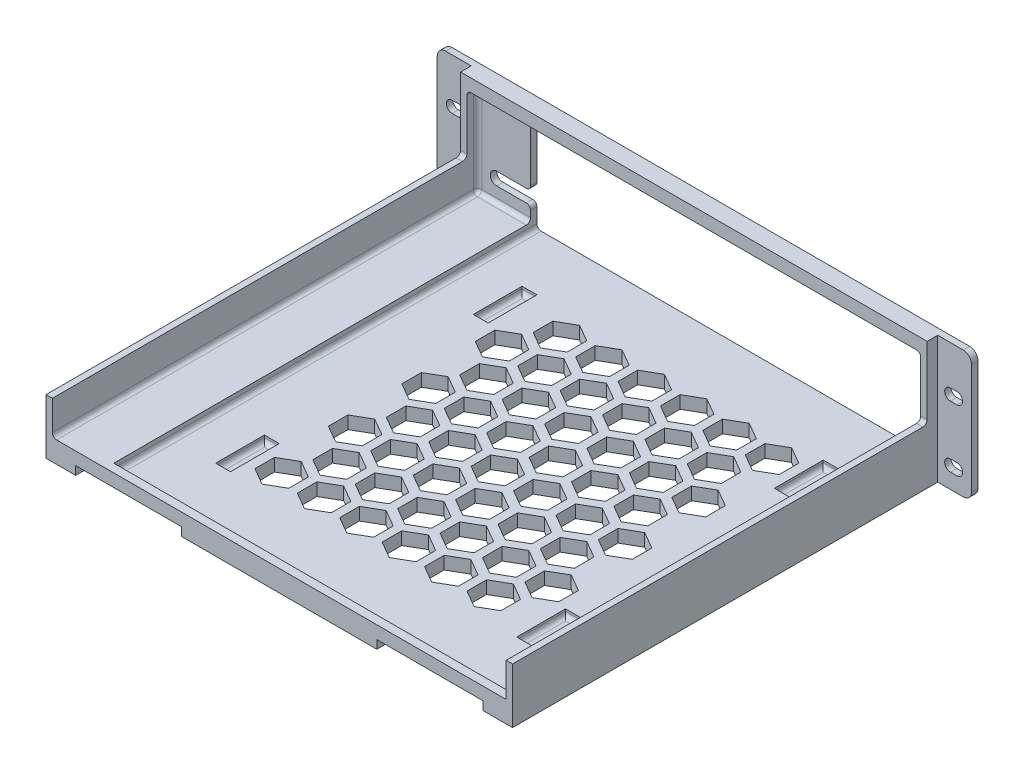
SolidWorks part; units mm, degrees
ref_plane "Front Plane" through (0, 0, 0) normal (0, 0, 1) x (1, 0, 0)
ref_plane "Top Plane" through (0, 0, 0) normal (0, 1, 0) x (1, 0, 0)
ref_plane "Right Plane" through (0, 0, 0) normal (1, 0, 0) x (0, 0, -1)
sketch "Sketch2" plane through (0, 0, 0) normal (0, 0, 1) x (1, 0, 0)
  line L0 (16, 106.2116) -> (16, -100.2906) construction
  line L1 (0, 0) -> (252, 0)
  line L2 (0, 0) -> (0, 60)
  line L3 (0, 60) -> (252, 60)
  line L4 (252, 0) -> (252, 60)
  line L5 (236, 110.5998) -> (236, -45.5674) construction
  line L6 (245, 38.8) -> (242, 38.8) construction
  line L7 (245, 36.1) -> (242, 36.1)
  line L8 (245, 41.5) -> (242, 41.5)
  line L9 (242, 9.8) -> (245, 9.8) construction
  line L10 (242, 12.5) -> (245, 12.5)
  line L11 (242, 7.1) -> (245, 7.1)
  line L12 (7, 38.8) -> (10, 38.8) construction
  line L13 (7, 41.5) -> (10, 41.5)
  line L14 (7, 36.1) -> (10, 36.1)
  line L15 (7, 9.8) -> (10, 9.8) construction
  line L16 (7, 12.5) -> (10, 12.5)
  line L17 (7, 7.1) -> (10, 7.1)
  arc A4 (245, 36.1) -> (245, 41.5) centre (245, 38.8) ccw
  arc A5 (242, 41.5) -> (242, 36.1) centre (242, 38.8) ccw
  arc A6 (242, 12.5) -> (242, 7.1) centre (242, 9.8) ccw
  arc A7 (245, 7.1) -> (245, 12.5) centre (245, 9.8) ccw
  arc A8 (7, 41.5) -> (7, 36.1) centre (7, 38.8) ccw
  arc A9 (10, 36.1) -> (10, 41.5) centre (10, 38.8) ccw
  arc A10 (7, 12.5) -> (7, 7.1) centre (7, 9.8) ccw
  arc A11 (10, 7.1) -> (10, 12.5) centre (10, 9.8) ccw
  point P8 (8.5, 38.8)
  point P17 (243.5, 38.8)
  point P22 (243.5, 9.8)
  point P30 (8.5, 9.8)
  point P37 (0, 0)
  point P38 (0, 0)
  dimension "D5" = 7
  dimension "D10" = 29
  dimension "D6" = 2.7
  dimension "D1" = 16
  dimension "D2" = 16
  dimension "D3" = 220
  dimension "D4" = 60
  dimension "D7" = 6
  dimension "D8" = 7
  dimension "D9" = 21.2
  dimension "D11" = 6
extrude "Boss-Extrude1" add sketch "Sketch2" along normal blind 3
sketch "Sketch3" plane through (0, 0, 3) normal (0, 0, 1) x (1, 0, 0)
  line L0 (0, 0) -> (252, 0) construction
  line L1 (16, 0) -> (236, 0)
  line L2 (16, 0) -> (16, 6)
  line L3 (16, 6) -> (236, 6)
  line L4 (236, 0) -> (236, 6)
  line L7 (16, 0) -> (0, 0) construction
  line L8 (236, 0) -> (252, 0) construction
  dimension "D1" = 220
  dimension "D3" = 6
extrude "Boss-Extrude2" add sketch "Sketch3" along normal blind 200.5
sketch "Sketch6" plane through (0, 0, 0) normal (0, 0, -1) x (-1, 0, 0)
  line L0 (0, 0) -> (-252, 0) construction
  line L1 (-233, 6) -> (-44, 6)
  line L2 (-233, 6) -> (-233, 54)
  line L3 (-233, 54) -> (-44, 54)
  line L4 (-44, 6) -> (-44, 54)
  line L5 (-252, 0) -> (-252, 60) construction
  dimension "D1" = 6
  dimension "D2" = 48
  dimension "D3" = 189
  dimension "D4" = 19
extrude "Cut-Extrude1" cut sketch "Sketch6" against normal blind 4
sketch "Sketch9" plane through (0, 0, 0) normal (0, 0, -1) x (-1, 0, 0)
  line L0 (0, 60) -> (0, 0) construction
  line L2 (-20, 4.4578) -> (-20, 43.1358) construction
  line L5 (-233, 6) -> (-44, 6) construction
  line L6 (-28, 23) -> (-44, 23)
  line L7 (-44, 6) -> (-44, 54) construction
  line L8 (-44, 17) -> (-28, 17)
  line L9 (-44, 23) -> (-44, 17)
  arc A1 (-28, 17) -> (-28, 23) centre (-28, 20) ccw
  dimension "D2" = 6
  dimension "D1" = 20
  dimension "D3" = 14
  dimension "D4" = 16
extrude "Cut-Extrude11" cut sketch "Sketch9" against normal blind 3
sketch "Sketch10" plane through (0, 0, 3) normal (0, 0, 1) x (1, 0, 0)
  line L1 (16, 6) -> (19, 6)
  line L2 (16, 6) -> (16, 26)
  line L3 (16, 26) -> (19, 26)
  line L4 (19, 6) -> (19, 26)
  line L5 (236, 6) -> (233, 6)
  line L6 (236, 6) -> (236, 26)
  line L7 (236, 26) -> (233, 26)
  line L8 (233, 6) -> (233, 26)
  line L9 (233, 54) -> (233, 6) construction
  dimension "D1" = 3
  dimension "D2" = 20
  dimension "D3" = 20
extrude "Boss-Extrude7" add sketch "Sketch10" along normal blind 200.5
sketch "Sketch15" plane through (0, 0, 3) normal (0, 0, 1) x (1, 0, 0)
  line L0 (236, 26) -> (236, 60)
  line L1 (252, 60) -> (0, 60) construction
  line L2 (236, 60) -> (16, 60)
  line L3 (16, 60) -> (16, 26)
  line L4 (16, 26) -> (19, 26)
  line L5 (19, 26) -> (19, 54)
  line L6 (19, 54) -> (233, 54)
  line L7 (233, 54) -> (233, 26)
  line L8 (233, 54) -> (233, 26) construction
  line L9 (233, 26) -> (236, 26)
extrude "Boss-Extrude8" add sketch "Sketch15" along normal blind 5
sketch "Sketch11" plane through (0, 6, 0) normal (0, 1, 0) x (1, 0, 0)
  line L1 (213, -27) -> (206, -27)
  line L2 (213, -27) -> (213, -50)
  line L3 (213, -50) -> (206, -50)
  line L4 (206, -27) -> (206, -50)
  line L5 (233, -203.5) -> (233, 0) construction
  line L6 (44, -3) -> (44, 0) construction
  line L7 (64, -27) -> (71, -27)
  line L8 (64, -27) -> (64, -50)
  line L9 (64, -50) -> (71, -50)
  line L10 (71, -27) -> (71, -50)
  line L11 (213, -171.5) -> (206, -171.5)
  line L12 (213, -171.5) -> (213, -148.5)
  line L13 (213, -148.5) -> (206, -148.5)
  line L14 (206, -171.5) -> (206, -148.5)
  line L15 (64, -148.5) -> (71, -148.5)
  line L16 (64, -148.5) -> (64, -171.5)
  line L17 (64, -171.5) -> (71, -171.5)
  line L18 (71, -148.5) -> (71, -171.5)
  line L19 (233, 0) -> (44, 0) construction
  dimension "D1" = 20
  dimension "D2" = 20
  dimension "D3" = 7
  dimension "D4" = 27
  dimension "D5" = 50
  dimension "D6" = 148.5
  dimension "D7" = 171.5
extrude "Cut-Extrude12" cut sketch "Sketch11" against normal blind 3
sketch "Sketch13" plane through (0, 6, 0) normal (0, 1, 0) x (1, 0, 0)
  line L72 (93.5, -82.5068) -> (91.5, -85.9709) construction
  line L73 (93.5, -47.8658) -> (91.5, -51.3299) construction
  line L74 (95.5, -51.3299) -> (91.5, -51.3299) construction
  line L75 (95.5, -51.3299) -> (93.5, -47.8658) construction
  line L76 (181.5, -43.247) -> (183.5, -46.7111) construction
  line L77 (185.5, -43.247) -> (183.5, -46.7111) construction
  line L78 (185.5, -43.247) -> (181.5, -43.247) construction
  line L79 (95.5, -85.9709) -> (91.5, -85.9709) construction
  line L80 (95.5, -85.9709) -> (93.5, -82.5068) construction
  line L81 (181.5, -77.888) -> (183.5, -81.3521) construction
  line L82 (185.5, -77.888) -> (183.5, -81.3521) construction
  line L83 (185.5, -77.888) -> (181.5, -77.888) construction
  line L84 (91.5, -60.5675) -> (95.5, -60.5675) construction
  line L85 (93.5, -64.0316) -> (91.5, -60.5675) construction
  line L86 (93.5, -64.0316) -> (95.5, -60.5675) construction
  line L87 (93.5, -151.7889) -> (91.5, -155.253) construction
  line L88 (93.5, -117.1479) -> (91.5, -120.612) construction
  line L89 (95.5, -120.612) -> (91.5, -120.612) construction
  line L90 (95.5, -120.612) -> (93.5, -117.1479) construction
  line L91 (181.5, -112.5291) -> (183.5, -115.9932) construction
  line L92 (185.5, -112.5291) -> (183.5, -115.9932) construction
  line L93 (185.5, -112.5291) -> (181.5, -112.5291) construction
  line L94 (95.5, -155.253) -> (91.5, -155.253) construction
  line L95 (95.5, -155.253) -> (93.5, -151.7889) construction
  line L96 (181.5, -147.1701) -> (183.5, -150.6342) construction
  line L97 (185.5, -147.1701) -> (183.5, -150.6342) construction
  line L98 (185.5, -147.1701) -> (181.5, -147.1701) construction
  line L99 (91.5, -129.8496) -> (95.5, -129.8496) construction
  line L100 (93.5, -133.3137) -> (91.5, -129.8496) construction
  line L101 (93.5, -133.3137) -> (95.5, -129.8496) construction
  line L102 (91.5, -95.2085) -> (95.5, -95.2085) construction
  line L103 (93.5, -98.6726) -> (91.5, -95.2085) construction
  line L104 (93.5, -98.6726) -> (95.5, -95.2085) construction
  line L105 (75.5, -168.2118) -> (75.5, -145.0225) construction
  line L106 (201.5, -150.8913) -> (201.5, -127.7019) construction
  line L107 (206, -27) -> (201.5, -27) construction
  line L108 (71, -27) -> (75.5, -27) construction
  line L109 (83.5, -29.3906) -> (183.5, -29.3906) construction
  line L110 (64, -29.3906) -> (64, -27) construction
  line L111 (173.5, -169.1094) -> (73.5, -169.1094) construction
  line L112 (64, -27) -> (64, -50) construction
  line L113 (64, -171.5) -> (64, -169.1094) construction
  line B0 (113.5, -47.8658) -> (121.5, -43.247)
  line B1 (93.5, -47.8658) -> (101.5, -43.247)
  line B2 (101.5, -43.247) -> (101.5, -34.0094)
  line B3 (101.5, -34.0094) -> (93.5, -29.3906)
  line B4 (93.5, -29.3906) -> (85.5, -34.0094)
  line B5 (85.5, -34.0094) -> (85.5, -43.247)
  line B6 (85.5, -43.247) -> (93.5, -47.8658)
  line B7 (121.5, -43.247) -> (121.5, -34.0094)
  line B8 (121.5, -34.0094) -> (113.5, -29.3906)
  line B9 (113.5, -29.3906) -> (105.5, -34.0094)
  line B10 (105.5, -34.0094) -> (105.5, -43.247)
  line B11 (105.5, -43.247) -> (113.5, -47.8658)
  line B12 (133.5, -47.8658) -> (141.5, -43.247)
  line B13 (141.5, -43.247) -> (141.5, -34.0094)
  line B14 (141.5, -34.0094) -> (133.5, -29.3906)
  line B15 (133.5, -29.3906) -> (125.5, -34.0094)
  line B16 (125.5, -34.0094) -> (125.5, -43.247)
  line B17 (125.5, -43.247) -> (133.5, -47.8658)
  line B18 (153.5, -47.8658) -> (161.5, -43.247)
  line B19 (161.5, -43.247) -> (161.5, -34.0094)
  line B20 (161.5, -34.0094) -> (153.5, -29.3906)
  line B21 (153.5, -29.3906) -> (145.5, -34.0094)
  line B22 (145.5, -34.0094) -> (145.5, -43.247)
  line B23 (145.5, -43.247) -> (153.5, -47.8658)
  line B24 (173.5, -47.8658) -> (181.5, -43.247)
  line B25 (181.5, -43.247) -> (181.5, -34.0094)
  line B26 (181.5, -34.0094) -> (173.5, -29.3906)
  line B27 (173.5, -29.3906) -> (165.5, -34.0094)
  line B28 (165.5, -34.0094) -> (165.5, -43.247)
  line B29 (165.5, -43.247) -> (173.5, -47.8658)
  line B30 (193.5, -47.8658) -> (201.5, -43.247)
  line B31 (201.5, -43.247) -> (201.5, -34.0094)
  line B32 (201.5, -34.0094) -> (193.5, -29.3906)
  line B33 (193.5, -29.3906) -> (185.5, -34.0094)
  line B34 (185.5, -34.0094) -> (185.5, -43.247)
  line B35 (185.5, -43.247) -> (193.5, -47.8658)
  circle B36 centre (93.5, -38.6282) radius 8 construction
  circle B37 centre (113.5, -38.6282) radius 8 construction
  circle B38 centre (133.5, -38.6282) radius 8 construction
  circle B39 centre (153.5, -38.6282) radius 8 construction
  circle B40 centre (173.5, -38.6282) radius 8 construction
  circle B41 centre (193.5, -38.6282) radius 8 construction
  line B42 (103.5, -65.1863) -> (111.5, -60.5675)
  line B43 (83.5, -65.1863) -> (91.5, -60.5675)
  line B44 (91.5, -60.5675) -> (91.5, -51.3299)
  line B45 (91.5, -51.3299) -> (83.5, -46.7111)
  line B46 (83.5, -46.7111) -> (75.5, -51.3299)
  line B47 (75.5, -51.3299) -> (75.5, -60.5675)
  line B48 (75.5, -60.5675) -> (83.5, -65.1863)
  line B49 (111.5, -60.5675) -> (111.5, -51.3299)
  line B50 (111.5, -51.3299) -> (103.5, -46.7111)
  line B51 (103.5, -46.7111) -> (95.5, -51.3299)
  line B52 (95.5, -51.3299) -> (95.5, -60.5675)
  line B53 (95.5, -60.5675) -> (103.5, -65.1863)
  line B54 (123.5, -65.1863) -> (131.5, -60.5675)
  line B55 (131.5, -60.5675) -> (131.5, -51.3299)
  line B56 (131.5, -51.3299) -> (123.5, -46.7111)
  line B57 (123.5, -46.7111) -> (115.5, -51.3299)
  line B58 (115.5, -51.3299) -> (115.5, -60.5675)
  line B59 (115.5, -60.5675) -> (123.5, -65.1863)
  line B60 (143.5, -65.1863) -> (151.5, -60.5675)
  line B61 (151.5, -60.5675) -> (151.5, -51.3299)
  line B62 (151.5, -51.3299) -> (143.5, -46.7111)
  line B63 (143.5, -46.7111) -> (135.5, -51.3299)
  line B64 (135.5, -51.3299) -> (135.5, -60.5675)
  line B65 (135.5, -60.5675) -> (143.5, -65.1863)
  line B66 (163.5, -65.1863) -> (171.5, -60.5675)
  line B67 (171.5, -60.5675) -> (171.5, -51.3299)
  line B68 (171.5, -51.3299) -> (163.5, -46.7111)
  line B69 (163.5, -46.7111) -> (155.5, -51.3299)
  line B70 (155.5, -51.3299) -> (155.5, -60.5675)
  line B71 (155.5, -60.5675) -> (163.5, -65.1863)
  line B72 (183.5, -65.1863) -> (191.5, -60.5675)
  line B73 (191.5, -60.5675) -> (191.5, -51.3299)
  line B74 (191.5, -51.3299) -> (183.5, -46.7111)
  line B75 (183.5, -46.7111) -> (175.5, -51.3299)
  line B76 (175.5, -51.3299) -> (175.5, -60.5675)
  line B77 (175.5, -60.5675) -> (183.5, -65.1863)
  line B78 (113.5, -82.5068) -> (121.5, -77.888)
  line B79 (93.5, -82.5068) -> (101.5, -77.888)
  line B80 (101.5, -77.888) -> (101.5, -68.6504)
  line B81 (101.5, -68.6504) -> (93.5, -64.0316)
  line B82 (93.5, -64.0316) -> (85.5, -68.6504)
  line B83 (85.5, -68.6504) -> (85.5, -77.888)
  line B84 (85.5, -77.888) -> (93.5, -82.5068)
  line B85 (121.5, -77.888) -> (121.5, -68.6504)
  line B86 (121.5, -68.6504) -> (113.5, -64.0316)
  line B87 (113.5, -64.0316) -> (105.5, -68.6504)
  line B88 (105.5, -68.6504) -> (105.5, -77.888)
  line B89 (105.5, -77.888) -> (113.5, -82.5068)
  line B90 (133.5, -82.5068) -> (141.5, -77.888)
  line B91 (141.5, -77.888) -> (141.5, -68.6504)
  line B92 (141.5, -68.6504) -> (133.5, -64.0316)
  line B93 (133.5, -64.0316) -> (125.5, -68.6504)
  line B94 (125.5, -68.6504) -> (125.5, -77.888)
  line B95 (125.5, -77.888) -> (133.5, -82.5068)
  line B96 (153.5, -82.5068) -> (161.5, -77.888)
  line B97 (161.5, -77.888) -> (161.5, -68.6504)
  line B98 (161.5, -68.6504) -> (153.5, -64.0316)
  line B99 (153.5, -64.0316) -> (145.5, -68.6504)
  line B100 (145.5, -68.6504) -> (145.5, -77.888)
  line B101 (145.5, -77.888) -> (153.5, -82.5068)
  line B102 (173.5, -82.5068) -> (181.5, -77.888)
  line B103 (181.5, -77.888) -> (181.5, -68.6504)
  line B104 (181.5, -68.6504) -> (173.5, -64.0316)
  line B105 (173.5, -64.0316) -> (165.5, -68.6504)
  line B106 (165.5, -68.6504) -> (165.5, -77.888)
  line B107 (165.5, -77.888) -> (173.5, -82.5068)
  line B108 (193.5, -82.5068) -> (201.5, -77.888)
  line B109 (201.5, -77.888) -> (201.5, -68.6504)
  line B110 (201.5, -68.6504) -> (193.5, -64.0316)
  line B111 (193.5, -64.0316) -> (185.5, -68.6504)
  line B112 (185.5, -68.6504) -> (185.5, -77.888)
  line B113 (185.5, -77.888) -> (193.5, -82.5068)
  line B114 (103.5, -99.8274) -> (111.5, -95.2085)
  line B115 (83.5, -99.8274) -> (91.5, -95.2085)
  line B116 (91.5, -95.2085) -> (91.5, -85.9709)
  line B117 (91.5, -85.9709) -> (83.5, -81.3521)
  line B118 (83.5, -81.3521) -> (75.5, -85.9709)
  line B119 (75.5, -85.9709) -> (75.5, -95.2085)
  line B120 (75.5, -95.2085) -> (83.5, -99.8274)
  line B121 (111.5, -95.2085) -> (111.5, -85.9709)
  line B122 (111.5, -85.9709) -> (103.5, -81.3521)
  line B123 (103.5, -81.3521) -> (95.5, -85.9709)
  line B124 (95.5, -85.9709) -> (95.5, -95.2085)
  line B125 (95.5, -95.2085) -> (103.5, -99.8274)
  line B126 (123.5, -99.8274) -> (131.5, -95.2085)
  line B127 (131.5, -95.2085) -> (131.5, -85.9709)
  line B128 (131.5, -85.9709) -> (123.5, -81.3521)
  line B129 (123.5, -81.3521) -> (115.5, -85.9709)
  line B130 (115.5, -85.9709) -> (115.5, -95.2085)
  line B131 (115.5, -95.2085) -> (123.5, -99.8274)
  line B132 (143.5, -99.8274) -> (151.5, -95.2085)
  line B133 (151.5, -95.2085) -> (151.5, -85.9709)
  line B134 (151.5, -85.9709) -> (143.5, -81.3521)
  line B135 (143.5, -81.3521) -> (135.5, -85.9709)
  line B136 (135.5, -85.9709) -> (135.5, -95.2085)
  line B137 (135.5, -95.2085) -> (143.5, -99.8274)
  line B138 (163.5, -99.8274) -> (171.5, -95.2085)
  line B139 (171.5, -95.2085) -> (171.5, -85.9709)
  line B140 (171.5, -85.9709) -> (163.5, -81.3521)
  line B141 (163.5, -81.3521) -> (155.5, -85.9709)
  line B142 (155.5, -85.9709) -> (155.5, -95.2085)
  line B143 (155.5, -95.2085) -> (163.5, -99.8274)
  line B144 (183.5, -99.8274) -> (191.5, -95.2085)
  line B145 (191.5, -95.2085) -> (191.5, -85.9709)
  line B146 (191.5, -85.9709) -> (183.5, -81.3521)
  line B147 (183.5, -81.3521) -> (175.5, -85.9709)
  line B148 (175.5, -85.9709) -> (175.5, -95.2085)
  line B149 (175.5, -95.2085) -> (183.5, -99.8274)
  line B150 (113.5, -117.1479) -> (121.5, -112.5291)
  line B151 (93.5, -117.1479) -> (101.5, -112.5291)
  line B152 (101.5, -112.5291) -> (101.5, -103.2915)
  line B153 (101.5, -103.2915) -> (93.5, -98.6726)
  line B154 (93.5, -98.6726) -> (85.5, -103.2915)
  line B155 (85.5, -103.2915) -> (85.5, -112.5291)
  line B156 (85.5, -112.5291) -> (93.5, -117.1479)
  line B157 (121.5, -112.5291) -> (121.5, -103.2915)
  line B158 (121.5, -103.2915) -> (113.5, -98.6726)
  line B159 (113.5, -98.6726) -> (105.5, -103.2915)
  line B160 (105.5, -103.2915) -> (105.5, -112.5291)
  line B161 (105.5, -112.5291) -> (113.5, -117.1479)
  line B162 (133.5, -117.1479) -> (141.5, -112.5291)
  line B163 (141.5, -112.5291) -> (141.5, -103.2915)
  line B164 (141.5, -103.2915) -> (133.5, -98.6726)
  line B165 (133.5, -98.6726) -> (125.5, -103.2915)
  line B166 (125.5, -103.2915) -> (125.5, -112.5291)
  line B167 (125.5, -112.5291) -> (133.5, -117.1479)
  line B168 (153.5, -117.1479) -> (161.5, -112.5291)
  line B169 (161.5, -112.5291) -> (161.5, -103.2915)
  line B170 (161.5, -103.2915) -> (153.5, -98.6726)
  line B171 (153.5, -98.6726) -> (145.5, -103.2915)
  line B172 (145.5, -103.2915) -> (145.5, -112.5291)
  line B173 (145.5, -112.5291) -> (153.5, -117.1479)
  line B174 (173.5, -117.1479) -> (181.5, -112.5291)
  line B175 (181.5, -112.5291) -> (181.5, -103.2915)
  line B176 (181.5, -103.2915) -> (173.5, -98.6726)
  line B177 (173.5, -98.6726) -> (165.5, -103.2915)
  line B178 (165.5, -103.2915) -> (165.5, -112.5291)
  line B179 (165.5, -112.5291) -> (173.5, -117.1479)
  line B180 (193.5, -117.1479) -> (201.5, -112.5291)
  line B181 (201.5, -112.5291) -> (201.5, -103.2915)
  line B182 (201.5, -103.2915) -> (193.5, -98.6726)
  line B183 (193.5, -98.6726) -> (185.5, -103.2915)
  line B184 (185.5, -103.2915) -> (185.5, -112.5291)
  line B185 (185.5, -112.5291) -> (193.5, -117.1479)
  line B186 (103.5, -134.4684) -> (111.5, -129.8496)
  line B187 (83.5, -134.4684) -> (91.5, -129.8496)
  line B188 (91.5, -129.8496) -> (91.5, -120.612)
  line B189 (91.5, -120.612) -> (83.5, -115.9932)
  line B190 (83.5, -115.9932) -> (75.5, -120.612)
  line B191 (75.5, -120.612) -> (75.5, -129.8496)
  line B192 (75.5, -129.8496) -> (83.5, -134.4684)
  line B193 (111.5, -129.8496) -> (111.5, -120.612)
  line B194 (111.5, -120.612) -> (103.5, -115.9932)
  line B195 (103.5, -115.9932) -> (95.5, -120.612)
  line B196 (95.5, -120.612) -> (95.5, -129.8496)
  line B197 (95.5, -129.8496) -> (103.5, -134.4684)
  line B198 (123.5, -134.4684) -> (131.5, -129.8496)
  line B199 (131.5, -129.8496) -> (131.5, -120.612)
  line B200 (131.5, -120.612) -> (123.5, -115.9932)
  line B201 (123.5, -115.9932) -> (115.5, -120.612)
  line B202 (115.5, -120.612) -> (115.5, -129.8496)
  line B203 (115.5, -129.8496) -> (123.5, -134.4684)
  line B204 (143.5, -134.4684) -> (151.5, -129.8496)
  line B205 (151.5, -129.8496) -> (151.5, -120.612)
  line B206 (151.5, -120.612) -> (143.5, -115.9932)
  line B207 (143.5, -115.9932) -> (135.5, -120.612)
  line B208 (135.5, -120.612) -> (135.5, -129.8496)
  line B209 (135.5, -129.8496) -> (143.5, -134.4684)
  line B210 (163.5, -134.4684) -> (171.5, -129.8496)
  line B211 (171.5, -129.8496) -> (171.5, -120.612)
  line B212 (171.5, -120.612) -> (163.5, -115.9932)
  line B213 (163.5, -115.9932) -> (155.5, -120.612)
  line B214 (155.5, -120.612) -> (155.5, -129.8496)
  line B215 (155.5, -129.8496) -> (163.5, -134.4684)
  line B216 (183.5, -134.4684) -> (191.5, -129.8496)
  line B217 (191.5, -129.8496) -> (191.5, -120.612)
  line B218 (191.5, -120.612) -> (183.5, -115.9932)
  line B219 (183.5, -115.9932) -> (175.5, -120.612)
  line B220 (175.5, -120.612) -> (175.5, -129.8496)
  line B221 (175.5, -129.8496) -> (183.5, -134.4684)
  line B222 (113.5, -151.7889) -> (121.5, -147.1701)
  line B223 (93.5, -151.7889) -> (101.5, -147.1701)
  line B224 (101.5, -147.1701) -> (101.5, -137.9325)
  line B225 (101.5, -137.9325) -> (93.5, -133.3137)
  line B226 (93.5, -133.3137) -> (85.5, -137.9325)
  line B227 (85.5, -137.9325) -> (85.5, -147.1701)
  line B228 (85.5, -147.1701) -> (93.5, -151.7889)
  line B229 (121.5, -147.1701) -> (121.5, -137.9325)
  line B230 (121.5, -137.9325) -> (113.5, -133.3137)
  line B231 (113.5, -133.3137) -> (105.5, -137.9325)
  line B232 (105.5, -137.9325) -> (105.5, -147.1701)
  line B233 (105.5, -147.1701) -> (113.5, -151.7889)
  line B234 (133.5, -151.7889) -> (141.5, -147.1701)
  line B235 (141.5, -147.1701) -> (141.5, -137.9325)
  line B236 (141.5, -137.9325) -> (133.5, -133.3137)
  line B237 (133.5, -133.3137) -> (125.5, -137.9325)
  line B238 (125.5, -137.9325) -> (125.5, -147.1701)
  line B239 (125.5, -147.1701) -> (133.5, -151.7889)
  line B240 (153.5, -151.7889) -> (161.5, -147.1701)
  line B241 (161.5, -147.1701) -> (161.5, -137.9325)
  line B242 (161.5, -137.9325) -> (153.5, -133.3137)
  line B243 (153.5, -133.3137) -> (145.5, -137.9325)
  line B244 (145.5, -137.9325) -> (145.5, -147.1701)
  line B245 (145.5, -147.1701) -> (153.5, -151.7889)
  line B246 (173.5, -151.7889) -> (181.5, -147.1701)
  line B247 (181.5, -147.1701) -> (181.5, -137.9325)
  line B248 (181.5, -137.9325) -> (173.5, -133.3137)
  line B249 (173.5, -133.3137) -> (165.5, -137.9325)
  line B250 (165.5, -137.9325) -> (165.5, -147.1701)
  line B251 (165.5, -147.1701) -> (173.5, -151.7889)
  line B252 (193.5, -151.7889) -> (201.5, -147.1701)
  line B253 (201.5, -147.1701) -> (201.5, -137.9325)
  line B254 (201.5, -137.9325) -> (193.5, -133.3137)
  line B255 (193.5, -133.3137) -> (185.5, -137.9325)
  line B256 (185.5, -137.9325) -> (185.5, -147.1701)
  line B257 (185.5, -147.1701) -> (193.5, -151.7889)
  line B258 (103.5, -169.1094) -> (111.5, -164.4906)
  line B259 (83.5, -169.1094) -> (91.5, -164.4906)
  line B260 (91.5, -164.4906) -> (91.5, -155.253)
  line B261 (91.5, -155.253) -> (83.5, -150.6342)
  line B262 (83.5, -150.6342) -> (75.5, -155.253)
  line B263 (75.5, -155.253) -> (75.5, -164.4906)
  line B264 (75.5, -164.4906) -> (83.5, -169.1094)
  line B265 (111.5, -164.4906) -> (111.5, -155.253)
  line B266 (111.5, -155.253) -> (103.5, -150.6342)
  line B267 (103.5, -150.6342) -> (95.5, -155.253)
  line B268 (95.5, -155.253) -> (95.5, -164.4906)
  line B269 (95.5, -164.4906) -> (103.5, -169.1094)
  line B270 (123.5, -169.1094) -> (131.5, -164.4906)
  line B271 (131.5, -164.4906) -> (131.5, -155.253)
  line B272 (131.5, -155.253) -> (123.5, -150.6342)
  line B273 (123.5, -150.6342) -> (115.5, -155.253)
  line B274 (115.5, -155.253) -> (115.5, -164.4906)
  line B275 (115.5, -164.4906) -> (123.5, -169.1094)
  line B276 (143.5, -169.1094) -> (151.5, -164.4906)
  line B277 (151.5, -164.4906) -> (151.5, -155.253)
  line B278 (151.5, -155.253) -> (143.5, -150.6342)
  line B279 (143.5, -150.6342) -> (135.5, -155.253)
  line B280 (135.5, -155.253) -> (135.5, -164.4906)
  line B281 (135.5, -164.4906) -> (143.5, -169.1094)
  line B282 (163.5, -169.1094) -> (171.5, -164.4906)
  line B283 (171.5, -164.4906) -> (171.5, -155.253)
  line B284 (171.5, -155.253) -> (163.5, -150.6342)
  line B285 (163.5, -150.6342) -> (155.5, -155.253)
  line B286 (155.5, -155.253) -> (155.5, -164.4906)
  line B287 (155.5, -164.4906) -> (163.5, -169.1094)
  line B288 (183.5, -169.1094) -> (191.5, -164.4906)
  line B289 (191.5, -164.4906) -> (191.5, -155.253)
  line B290 (191.5, -155.253) -> (183.5, -150.6342)
  line B291 (183.5, -150.6342) -> (175.5, -155.253)
  line B292 (175.5, -155.253) -> (175.5, -164.4906)
  line B293 (175.5, -164.4906) -> (183.5, -169.1094)
sketch_block_instance "Block1-1"
sketch_block "Block1" parameters "D1"=16
sketch_block_instance "Block1-2"
sketch_block_instance "Block1-3"
sketch_block_instance "Block1-4"
sketch_block_instance "Block1-6"
sketch_block_instance "Block1-7"
sketch_block_instance "Block1-8"
sketch_block_instance "Block1-9"
extrude "Cut-Extrude13" cut sketch "Sketch13" against normal blind 6
sketch "Sketch17" plane through (0, 6, 0) normal (0, 1, 0) x (1, 0, 0)
  line L0 (233, -203.5) -> (233, -8) construction
  line L1 (19, -203.5) -> (233, -203.5)
  line L3 (44, -199.5) -> (233, -199.5)
  line L4 (233, -203.5) -> (233, -199.5)
  line L9 (44, -199.5) -> (44, -3)
  line L12 (19, -3) -> (19, -203.5)
  line L14 (19, -3) -> (44, -3)
  line L16 (44, -3) -> (44, 0) construction
  dimension "D1" = 4
extrude "Boss-Extrude9" add sketch "Sketch17" along normal blind 4
sketch "Sketch18" plane through (0, 0, 203.5) normal (0, 0, 1) x (1, 0, 0)
  line L0 (16, 0) -> (236, 0) construction
  line L1 (172, 0) -> (222, 0)
  line L2 (172, 0) -> (172, 4)
  line L3 (172, 4) -> (222, 4)
  line L4 (222, 0) -> (222, 4)
  line L6 (0, 60) -> (0, 0) construction
  line L8 (30, 0) -> (80, 0)
  line L9 (30, 0) -> (30, 4)
  line L10 (30, 4) -> (80, 4)
  line L11 (80, 0) -> (80, 4)
  line L12 (252, 0) -> (252, 60) construction
  dimension "D1" = 4
  dimension "D2" = 30
  dimension "D3" = 30
  dimension "D4" = 50
  dimension "D5" = 50
  dimension "D6" = 4
extrude "Cut-Extrude14" cut sketch "Sketch18" against normal blind 4
fillet "Fillet1" radius 4 4 edges at (252, 0, 1.5) (252, 60, 1.5) (0, 0, 1.5) (0, 60, 1.5)
fillet "Fillet2" radius 2 13 edges at (44, 17, 1.5) (44, 23, 1.5) (19, 32, 3) (233, 6, 99.75) (19, 10, 103.25) (31.5, 10, 3) (31.5, 54, 3) (19, 54, 5.5) (234.5, 26, 8) (17.5, 26, 8) (233, 54, 4) (44, 6, 99.75) (44, 54, 1.5)
fillet "Fillet3" radius 2 16 edges at (67.5, 3, 148.5) (71, 3, 160) (67.5, 3, 171.5) (64, 3, 160) (209.5, 3, 171.5) (206, 3, 160) (209.5, 3, 148.5) (213, 3, 160) (209.5, 3, 50) (206, 3, 38.5) (209.5, 3, 27) (213, 3, 38.5) (67.5, 3, 27) (71, 3, 38.5) (67.5, 3, 50) (64, 3, 38.5)
